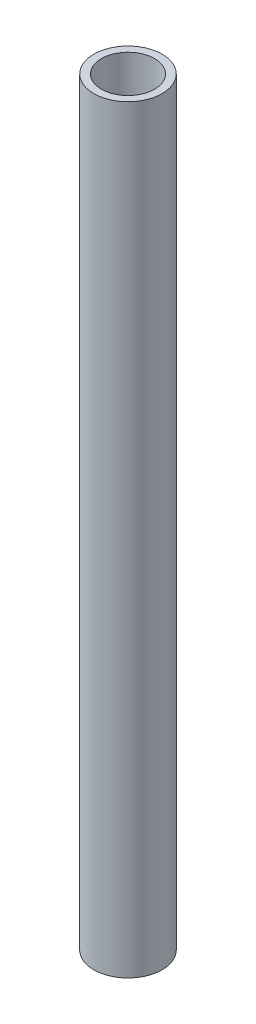
SolidWorks part; units mm, degrees
ref_plane "Front Plane" through (0, 0, 0) normal (0, 0, 1) x (1, 0, 0)
ref_plane "Top Plane" through (0, 0, 0) normal (0, 1, 0) x (1, 0, 0)
ref_plane "Right Plane" through (0, 0, 0) normal (1, 0, 0) x (0, 0, -1)
sketch "Sketch1" plane through (0, 0, 0) normal (0, 1, 0) x (1, 0, 0)
  circle A0 centre (0, 0) radius 3.5
  circle A1 centre (0, 0) radius 4.5
  dimension "D1" = 7
  dimension "D2" = 9
extrude "Boss-Extrude1" add sketch "Sketch1" along normal blind 100
